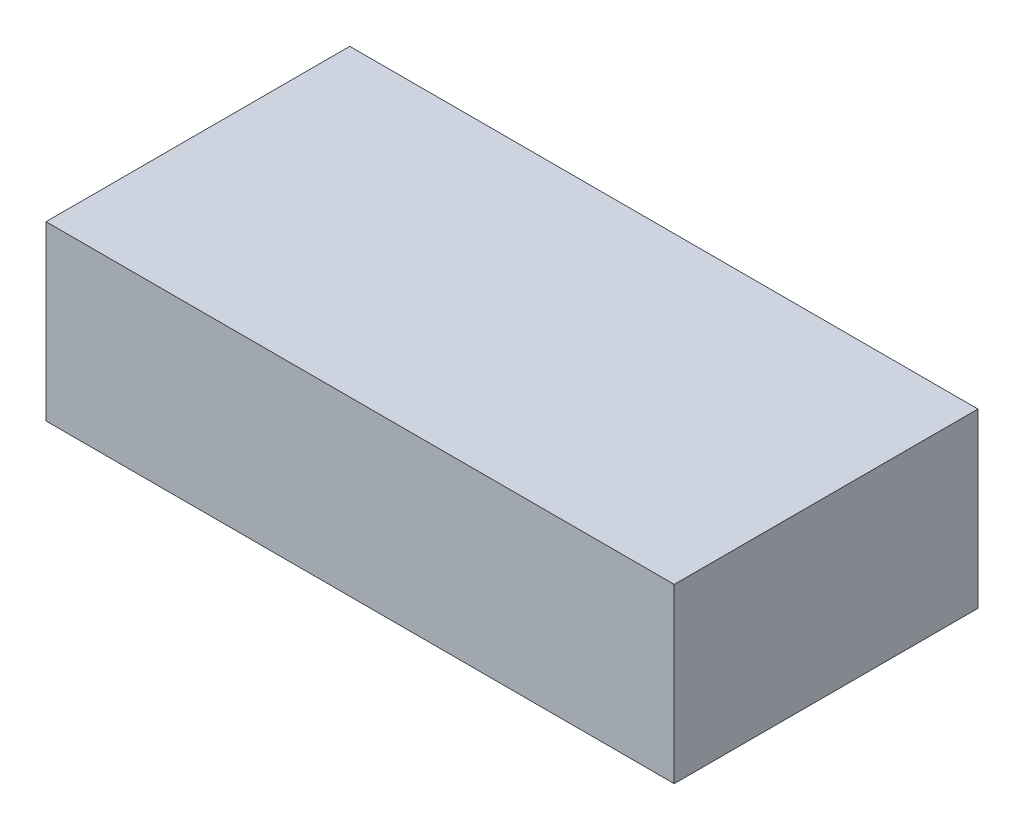
SolidWorks part; units mm, degrees
ref_plane "Front Plane" through (0, 0, 0) normal (0, 0, 1) x (1, 0, 0)
ref_plane "Top Plane" through (0, 0, 0) normal (0, 1, 0) x (1, 0, 0)
ref_plane "Right Plane" through (0, 0, 0) normal (1, 0, 0) x (0, 0, -1)
sketch "Sketch1" plane through (0, 0, 0) normal (0, 0, 1) x (1, 0, 0)
  line L1 (-30.4582, 18.6616) -> (-12.2582, 18.6616)
  line L2 (-30.4582, 18.6616) -> (-30.4582, 13.6616)
  line L3 (-30.4582, 13.6616) -> (-12.2582, 13.6616)
  line L4 (-12.2582, 18.6616) -> (-12.2582, 13.6616)
  line L5 (-30.4582, 18.6616) -> (-12.2582, 13.6616) construction
  line L6 (-30.4582, 13.6616) -> (-12.2582, 18.6616) construction
  point P4 (-21.3582, 16.1616)
  dimension "D1" = 18.2
  dimension "D2" = 5
extrude "Boss-Extrude1" add sketch "Sketch1" along normal blind 8.8
